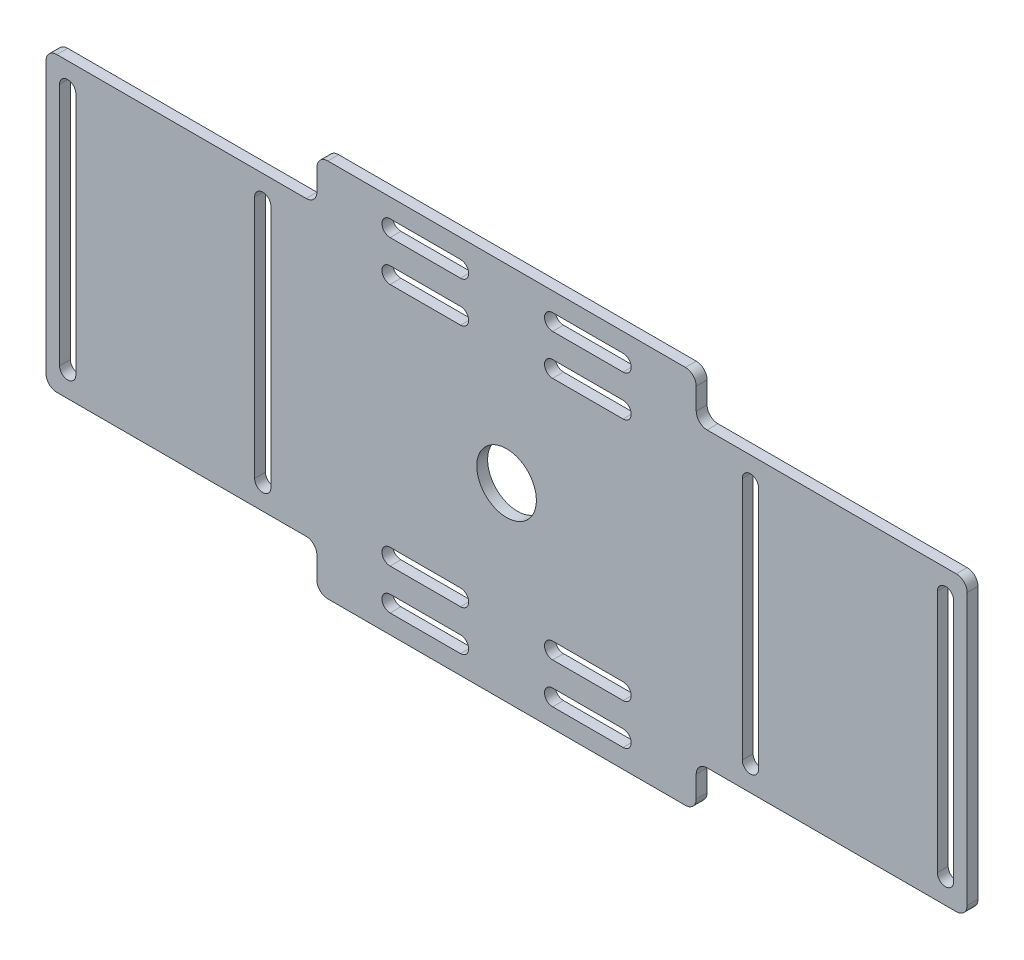
SolidWorks part; units mm, degrees
ref_plane "前基準面" through (0, 0, 0) normal (0, 0, 1) x (1, 0, 0)
ref_plane "上基準面" through (0, 0, 0) normal (0, 1, 0) x (1, 0, 0)
ref_plane "右基準面" through (0, 0, 0) normal (1, 0, 0) x (0, 0, -1)
sketch "草圖1" plane through (0, 0, 0) normal (0, 0, 1) x (1, 0, 0)
  line L1 (-85, 35) -> (85, 35)
  line L2 (-85, 35) -> (-85, -35)
  line L3 (-85, -35) -> (85, -35)
  line L4 (85, 35) -> (85, -35)
  line L5 (-85, 35) -> (85, -35) construction
  line L6 (-85, -35) -> (85, 35) construction
  point P0 (0, 0)
  dimension "D1" = 170
  dimension "D2" = 70
extrude "填料-伸長1" add sketch "草圖1" along normal blind 2
sketch "草圖2" plane through (0, 0, 2) normal (0, 0, 1) x (1, 0, 0)
  line L0 (-1000, 0) -> (49000, 0) construction
  line L1 (45, -986.1952) -> (45, 49013.8048) construction
  line L2 (-81, -962.7943) -> (-81, 49037.2057) construction
  line L3 (45, -22.5) -> (45, 22.5) construction
  line L4 (43.5, -22.5) -> (43.5, 22.5)
  line L5 (46.5, -22.5) -> (46.5, 22.5)
  line L6 (-45, -1000) -> (-45, 49000) construction
  line L7 (-45, -22.5) -> (-45, 22.5) construction
  line L8 (-46.5, -22.5) -> (-46.5, 22.5)
  line L9 (-43.5, -22.5) -> (-43.5, 22.5)
  line L10 (0, -1000) -> (0, 49000) construction
  line L11 (-1005.6924, 30) -> (48994.3076, 30) construction
  line L12 (-1002.3566, -30) -> (48997.6434, -30) construction
  line L13 (21.5, 30) -> (8.5, 30) construction
  line L16 (21.5, 28.5) -> (8.5, 28.5)
  line L19 (81, -968.4295) -> (81, 49031.5705) construction
  line L20 (-81, -22.5) -> (-81, 22.5) construction
  line L21 (-82.5, -22.5) -> (-82.5, 22.5)
  line L22 (-79.5, -22.5) -> (-79.5, 22.5)
  line L23 (81, -22.5) -> (81, 22.5) construction
  line L24 (79.5, -22.5) -> (79.5, 22.5)
  line L25 (82.5, -22.5) -> (82.5, 22.5)
  line L26 (21.5, 31.5) -> (8.5, 31.5)
  line L27 (21.5, 22.5) -> (8.5, 22.5) construction
  line L28 (21.5, 21) -> (8.5, 21)
  line L29 (21.5, 24) -> (8.5, 24)
  line L30 (-21.5, 30) -> (-8.5, 30) construction
  line L31 (-21.5, 28.5) -> (-8.5, 28.5)
  line L32 (-21.5, 31.5) -> (-8.5, 31.5)
  line L33 (-21.5, 22.5) -> (-8.5, 22.5) construction
  line L34 (-21.5, 21) -> (-8.5, 21)
  line L35 (-21.5, 24) -> (-8.5, 24)
  line L36 (21.5, -30) -> (8.5, -30) construction
  line L37 (21.5, -28.5) -> (8.5, -28.5)
  line L38 (21.5, -31.5) -> (8.5, -31.5)
  line L39 (21.5, -22.5) -> (8.5, -22.5) construction
  line L40 (21.5, -21) -> (8.5, -21)
  line L41 (21.5, -24) -> (8.5, -24)
  line L42 (-21.5, -30) -> (-8.5, -30) construction
  line L43 (-21.5, -28.5) -> (-8.5, -28.5)
  line L44 (-21.5, -31.5) -> (-8.5, -31.5)
  line L45 (-21.5, -22.5) -> (-8.5, -22.5) construction
  line L46 (-21.5, -21) -> (-8.5, -21)
  line L47 (-21.5, -24) -> (-8.5, -24)
  arc A0 (43.5, -22.5) -> (46.5, -22.5) centre (45, -22.5) ccw
  arc A1 (46.5, 22.5) -> (43.5, 22.5) centre (45, 22.5) ccw
  arc A2 (-46.5, -22.5) -> (-43.5, -22.5) centre (-45, -22.5) ccw
  arc A3 (-43.5, 22.5) -> (-46.5, 22.5) centre (-45, 22.5) ccw
  arc A12 (-82.5, -22.5) -> (-79.5, -22.5) centre (-81, -22.5) ccw
  arc A13 (-79.5, 22.5) -> (-82.5, 22.5) centre (-81, 22.5) ccw
  arc A14 (79.5, -22.5) -> (82.5, -22.5) centre (81, -22.5) ccw
  arc A15 (82.5, 22.5) -> (79.5, 22.5) centre (81, 22.5) ccw
  circle A16 centre (0, 0) radius 5.5
  arc A17 (21.5, 28.5) -> (21.5, 31.5) centre (21.5, 30) ccw
  arc A18 (8.5, 31.5) -> (8.5, 28.5) centre (8.5, 30) ccw
  arc A19 (21.5, 21) -> (21.5, 24) centre (21.5, 22.5) ccw
  arc A20 (8.5, 24) -> (8.5, 21) centre (8.5, 22.5) ccw
  arc A21 (-21.5, 28.5) -> (-21.5, 31.5) centre (-21.5, 30) cw
  arc A22 (-8.5, 31.5) -> (-8.5, 28.5) centre (-8.5, 30) cw
  arc A23 (-21.5, 21) -> (-21.5, 24) centre (-21.5, 22.5) cw
  arc A24 (-8.5, 24) -> (-8.5, 21) centre (-8.5, 22.5) cw
  arc A25 (21.5, -28.5) -> (21.5, -31.5) centre (21.5, -30) cw
  arc A26 (8.5, -31.5) -> (8.5, -28.5) centre (8.5, -30) cw
  arc A27 (21.5, -21) -> (21.5, -24) centre (21.5, -22.5) cw
  arc A28 (8.5, -24) -> (8.5, -21) centre (8.5, -22.5) cw
  arc A29 (-21.5, -28.5) -> (-21.5, -31.5) centre (-21.5, -30) ccw
  arc A30 (-8.5, -31.5) -> (-8.5, -28.5) centre (-8.5, -30) ccw
  arc A31 (-21.5, -21) -> (-21.5, -24) centre (-21.5, -22.5) ccw
  arc A32 (-8.5, -24) -> (-8.5, -21) centre (-8.5, -22.5) ccw
  point P9 (45, 0)
  point P16 (-45, 0)
  point P31 (15, 30)
  point P39 (15, 22.5)
  point P47 (-81, 0)
  point P54 (81, 0)
  point P63 (-15, 30)
  point P70 (-15, 22.5)
  point P77 (15, -30)
  point P84 (15, -22.5)
  point P91 (-15, -30)
  point P98 (-15, -22.5)
  dimension "D10" = 1.5
  dimension "D20" = 11
  dimension "D12" = 8.5
  dimension "D2" = 45
  dimension "D3" = 3
  dimension "D4" = 90
  dimension "D5" = 45
  dimension "D6" = 3
  dimension "D7" = 45
  dimension "D8" = 60
  dimension "D9" = 30
  dimension "D11" = 13
  dimension "D13" = 2
  dimension "D14" = 162
  dimension "D15" = 81
  dimension "D16" = 3
  dimension "D17" = 45
  dimension "D18" = 45
  dimension "D19" = 3
extrude "除料-伸長1" cut sketch "草圖2" against normal through all
sketch "草圖4" plane through (0, 0, 2) normal (0, 0, 1) x (1, 0, 0)
  line L0 (0, 52.0279) -> (0, -54.8062) construction
  line L1 (85, 35) -> (33, 35)
  line L2 (85, 35) -> (85, 25)
  line L3 (83, 27) -> (37, 27)
  line L4 (35, 33) -> (35, 29)
  line L5 (85, -35) -> (85, 35) construction
  line L6 (-98.2871, 0) -> (106.0141, 0) construction
  line L8 (35, -33) -> (35, -29)
  line L9 (83, -27) -> (37, -27)
  line L10 (85, -35) -> (85, -25)
  line L11 (85, -35) -> (33, -35)
  line L12 (-85, -35) -> (-33, -35)
  line L13 (-85, -35) -> (-85, -25)
  line L14 (-83, -27) -> (-37, -27)
  line L15 (-35, -33) -> (-35, -29)
  line L16 (-35, 33) -> (-35, 29)
  line L17 (-83, 27) -> (-37, 27)
  line L18 (-85, 35) -> (-85, 25)
  line L19 (-85, 35) -> (-33, 35)
  arc A0 (83, 27) -> (85, 25) centre (83, 25) cw
  arc A1 (37, 27) -> (35, 29) centre (37, 29) cw
  arc A2 (35, 33) -> (33, 35) centre (33, 33) ccw
  arc A3 (35, -33) -> (33, -35) centre (33, -33) cw
  arc A4 (37, -27) -> (35, -29) centre (37, -29) ccw
  arc A5 (83, -27) -> (85, -25) centre (83, -25) ccw
  arc A6 (-83, -27) -> (-85, -25) centre (-83, -25) cw
  arc A7 (-37, -27) -> (-35, -29) centre (-37, -29) cw
  arc A8 (-35, -33) -> (-33, -35) centre (-33, -33) ccw
  arc A9 (-35, 33) -> (-33, 35) centre (-33, 33) cw
  arc A10 (-37, 27) -> (-35, 29) centre (-37, 29) ccw
  arc A11 (-83, 27) -> (-85, 25) centre (-83, 25) ccw
  dimension "D1" = 2
  dimension "D2" = 2
  dimension "D3" = 2
  dimension "D4" = 52
  dimension "D5" = 8
extrude "除料-伸長2" cut sketch "草圖4" against normal through all
